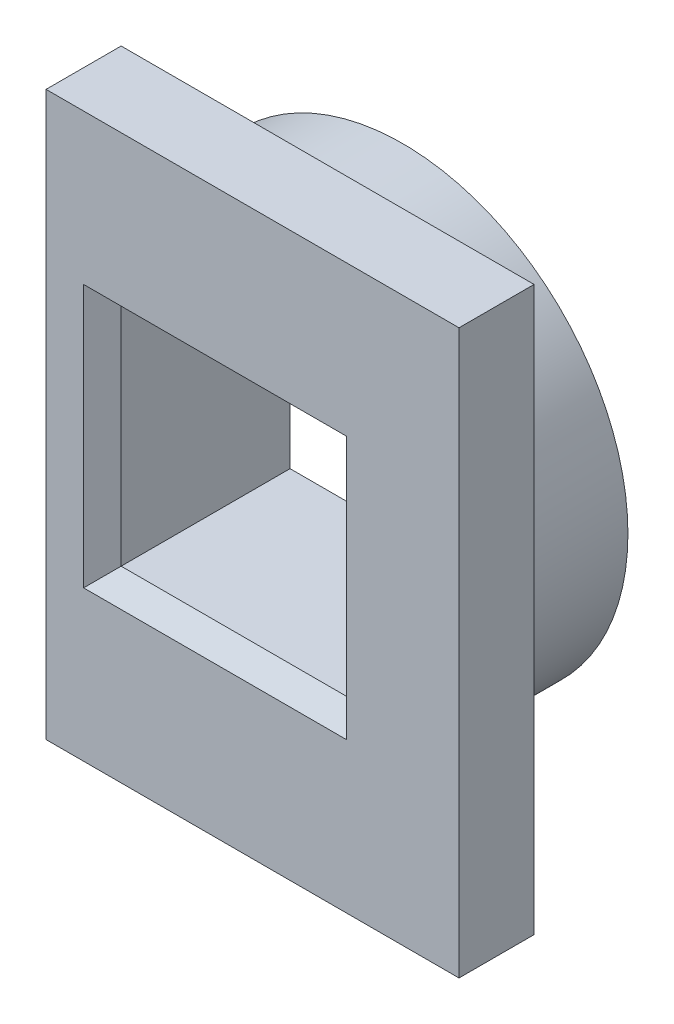
SolidWorks part; units mm, degrees
ref_plane "Front Plane" through (0, 0, 0) normal (0, 0, 1) x (1, 0, 0)
ref_plane "Top Plane" through (0, 0, 0) normal (0, 1, 0) x (1, 0, 0)
ref_plane "Right Plane" through (0, 0, 0) normal (1, 0, 0) x (0, 0, -1)
sketch "Sketch1" plane through (0, 0, 0) normal (0, 0, 1) x (1, 0, 0)
  circle A0 centre (0, 0) radius 6
  dimension "D1" = 12
extrude "Boss-Extrude1" add sketch "Sketch1" along normal blind 3
sketch "Sketch2" plane through (0, 0, 3) normal (0, 0, 1) x (1, 0, 0)
  line L1 (-4.5, 7.5) -> (6.5, 7.5)
  line L2 (-4.5, 7.5) -> (-4.5, -7.5)
  line L3 (-4.5, -7.5) -> (6.5, -7.5)
  line L4 (6.5, 7.5) -> (6.5, -7.5)
  point P4 (-4.5, 0)
  point P6 (1, 7.5)
  dimension "D1" = 15
  dimension "D2" = 0
  dimension "D3" = 11
  dimension "D4" = 1
extrude "Boss-Extrude2" add sketch "Sketch2" along normal blind 2
sketch "Sketch3" plane through (0, 0, 0) normal (0, 0, -1) x (-1, 0, 0)
  line L1 (-3, 3) -> (3, 3)
  line L2 (-3, 3) -> (-3, -3)
  line L3 (-3, -3) -> (3, -3)
  line L4 (3, 3) -> (3, -3)
  point P4 (-3, 0)
  point P6 (0, 3)
  dimension "D1" = 6
  dimension "D2" = 6
  dimension "D3" = 0
  dimension "D4" = 0
extrude "Cut-Extrude1" cut sketch "Sketch3" against normal through all
chamfer "Chamfer1" distance 0.5 angle 45 4 edges at (0, 3, 5) (3, 0, 5) (0, -3, 5) (-3, 0, 5)
